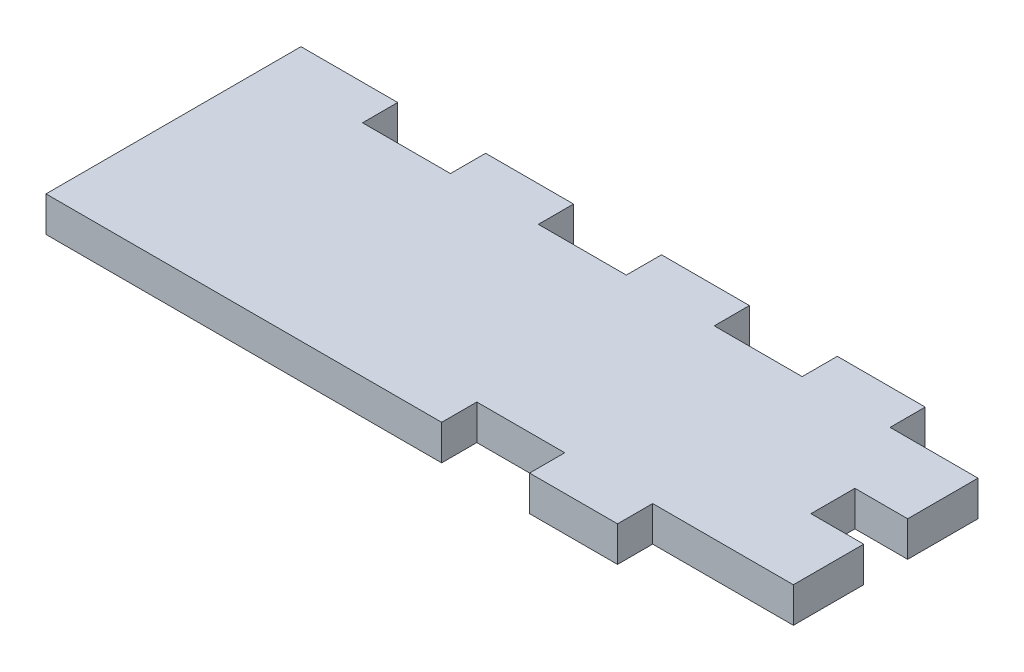
SolidWorks part; units mm, degrees
material "Maple"
ref_plane "Front Plane" through (0, 0, 0) normal (0, 0, 1) x (1, 0, 0)
ref_plane "Top Plane" through (0, 0, 0) normal (0, 1, 0) x (1, 0, 0)
ref_plane "Right Plane" through (0, 0, 0) normal (1, 0, 0) x (0, 0, -1)
sketch "Sketch1" plane through (0, 0, 0) normal (0, 1, 0) x (1, 0, 0)
  line L1 (0, 0) -> (75, 0)
  line L2 (0, 0) -> (0, -21)
  line L3 (0, -21) -> (75, -21)
  line L4 (75, 0) -> (75, -21)
  dimension "D1" = 75
  dimension "D2" = 21
extrude "Boss-Extrude1" add sketch "Sketch1" along normal blind 4
sketch "Sketch2" plane through (75, 0, 0) normal (1, 0, 0) x (0, 0, -1)
  line L0 (-21, 4) -> (0, 4) construction
  line L1 (-21, 4) -> (-13, 4)
  line L2 (-21, 4) -> (-21, 0)
  line L3 (-21, 0) -> (-13, 0)
  line L4 (-13, 4) -> (-13, 0)
  line L5 (-21, 0) -> (0, 0) construction
  line L6 (0, 4) -> (0, 0) construction
  line L7 (0, 4) -> (-8, 4)
  line L8 (0, 4) -> (0, 0)
  line L9 (0, 0) -> (-8, 0)
  line L10 (-8, 4) -> (-8, 0)
  line L11 (-21, 4) -> (-21, 0) construction
  dimension "D1" = 5
extrude "Boss-Extrude2" add sketch "Sketch2" along normal blind 6
sketch "Sketch3" plane through (0, 4, 0) normal (0, 1, 0) x (1, 0, 0)
  line L0 (81, 0) -> (0, 0) construction
  line L1 (71, 0) -> (61, 0)
  line L2 (71, 0) -> (71, 4)
  line L3 (71, 4) -> (61, 4)
  line L4 (61, 0) -> (61, 4)
  line L5 (81, 0) -> (81, -8) construction
  dimension "D1" = 10
  dimension "D2" = 4
  dimension "D3" = 10
extrude "Boss-Extrude3" add sketch "Sketch3" against normal through all
pattern_linear "LPattern1" count 4 spacing 20 along (-1, 0, 0) of "Boss-Extrude3"
sketch "Sketch4" plane through (0, 4, 0) normal (0, 1, 0) x (1, 0, 0)
  line L1 (1, 4) -> (0, 4)
  line L2 (1, 4) -> (1, 0)
  line L3 (1, 0) -> (0, 0)
  line L4 (0, 4) -> (0, 0)
extrude "Boss-Extrude4" add sketch "Sketch4" against normal through all
sketch "Sketch5" plane through (0, 4, 0) normal (0, 1, 0) x (1, 0, 0)
  line L0 (0, 4) -> (0, -21) construction
  line L1 (0, -21) -> (45, -21)
  line L2 (0, -21) -> (0, -25)
  line L3 (0, -25) -> (45, -25)
  line L4 (45, -21) -> (45, -25)
  line L5 (0, -21) -> (81, -21) construction
  line L7 (55, -25) -> (65, -25)
  line L8 (55, -25) -> (55, -21)
  line L9 (55, -21) -> (65, -21)
  line L10 (65, -25) -> (65, -21)
  dimension "D1" = 4
  dimension "D2" = 45
  dimension "D3" = 10
  dimension "D4" = 10
extrude "Boss-Extrude5" add sketch "Sketch5" against normal through all
